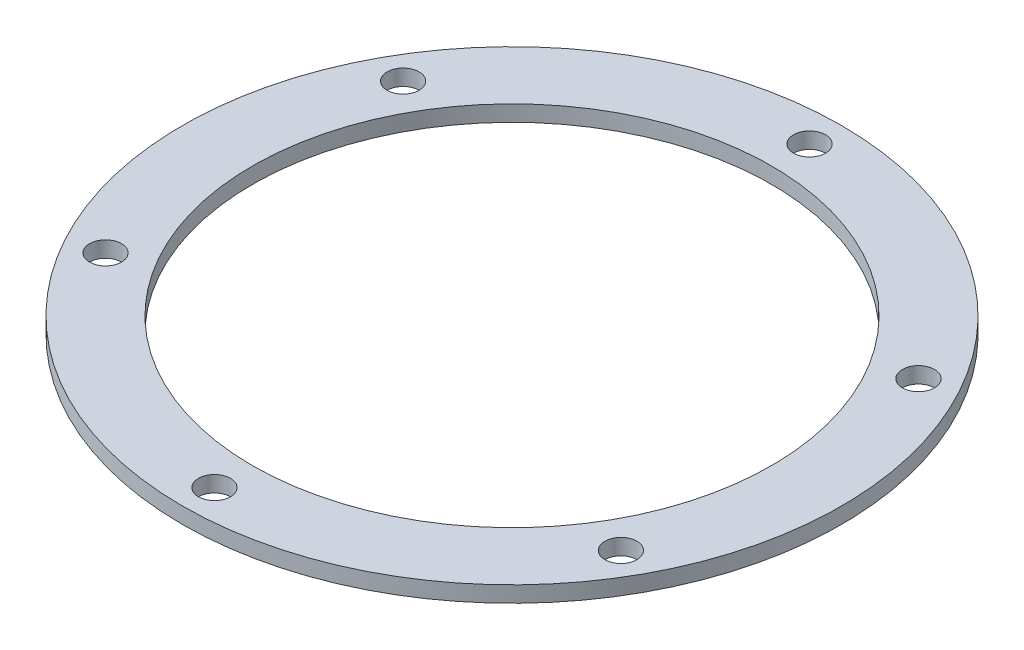
SolidWorks part; units mm, degrees
ref_plane "Front Plane" through (0, 0, 0) normal (0, 0, 1) x (1, 0, 0)
ref_plane "Top Plane" through (0, 0, 0) normal (0, 1, 0) x (1, 0, 0)
ref_plane "Right Plane" through (0, 0, 0) normal (1, 0, 0) x (0, 0, -1)
sketch "Sketch1" plane through (0, 0, 0) normal (0, 1, 0) x (1, 0, 0)
  circle A0 centre (0, 0) radius 41.195
  circle A1 centre (0, 0) radius 32.445
  circle A2 centre (0, 0) radius 37.195 construction
  circle A3 centre (0, 37.195) radius 2
  circle A4 centre (32.2118, 18.5975) radius 2
  circle A5 centre (32.2118, -18.5975) radius 2
  circle A6 centre (0, -37.195) radius 2
  circle A7 centre (-32.2118, -18.5975) radius 2
  circle A8 centre (-32.2118, 18.5975) radius 2
  point P16 (0, 0)
  point P18 (0, 0)
  dimension "D1" = 64.89
  dimension "D3" = 74.39
  dimension "D4" = 4
  dimension "D2" = 8.75
  dimension "D5" = 6
extrude "Boss-Extrude1" add sketch "Sketch1" along normal blind 2
equation "\"Ns\"= 20"
equation "\"Np\"= 40"
equation "\"Nr\"= \"Ns\" + 2 * \"Np\"'num teeth"
equation "\"num_planet\"= 3"
equation "\"module\"= 0.65"
equation "\"pressure angle\"= 20deg"
equation "\"h_a\"= 1 * \"module\"'addendum"
equation "\"h_b\"= 1.25 * \"module\"'dedendum"
equation "\"clr_tip_root\"= \"h_f\" - \"h_a\"'clearance of gear tooth tip and root"
equation "\"dp_s\"= \"module\" * \"Ns\"'PCD"
equation "\"db_s\"= \"dp_s\" * cos ( \"pressure angle\" )'base CD"
equation "\"fw_s_calc\"= 13mm'face width"
equation "\"alpha_s\"= sqr ( \"dp_s\" ^ 2 - \"db_s\" ^ 2 ) / \"db_s\" * 180 / pi - \"pressure angle\""
equation "\"beta_s\"= ( 360 / ( 4 * \"Ns\" ) - \"alpha_s\" ) * 2"
equation "\"dp_p\"= \"module\" * \"Np\"'PCD"
equation "\"db_p\"= \"dp_p\" * cos ( \"pressure angle\" )'base CD"
equation "\"fw_p\"= \"fw_r\""
equation "\"alpha_p\"= sqr ( \"dp_p\" ^ 2 - \"db_p\" ^ 2 ) / \"db_p\" * 180 / pi - \"pressure angle\""
equation "\"beta_p\"= ( 360 / ( 4 * \"Np\" ) - \"alpha_p\" ) * 2"
equation "\"pressure_angle\"= 20deg"
equation "\"h_f\"= 1.25 * \"module\"'dedendum"
equation "\"dp_r\"= \"module\" * \"Nr\"'PCD"
equation "\"db_r\"= \"dp_r\" * cos ( \"pressure_angle\" )'base CD"
equation "\"fw_r\"= 11.5mm'face width"
equation "\"alpha_r\"= sqr ( \"dp_r\" ^ 2 - \"db_r\" ^ 2 ) / \"db_r\" * 180 / pi - \"pressure_angle\""
equation "\"beta_r\"= ( 360 / ( 4 * \"Nr\" ) + \"alpha_r\" ) * 2"
equation "\"bearing_ID\"= \"module\" * ( \"Ns\" + \"Np\" ) + 10"
equation "\"bearing_OD\"= 1.18 * \"bearing_ID\" + 8.57"
equation "\"bearing_height\"= 0.09 * \"bearing_ID\" + 4.62"
equation "\"clearance_planet\"=1.5"
equation "\"case_dist\"= \"sec_carrier_thickness\" + \"clearance_planet\" + \"sun_coupler_hub_thickness\" - \"case_mounting_surface_height\""
equation "\"Motor_case_OD_max\"= \"case_mounting_PCD\" + \"case_mounting_hole_allen_socket_dia\" + \"clearance_case_mount_holes_shell_thickness\" * 2"
equation "\"case_mounting_PCD\"= \"motor_case_OD_base\" + \"case_mounting_hole_shift\" * 2"
equation "\"bearing mount thickness\"= \"output_mounting_hole_dia\" * 2"
equation "\"case_mounting_hole_dia\"=3"
equation "\"output_mounting_PCD\"= \"bearing_OD\" + \"bearing mount thickness\""
equation "\"output_mounting_hole_dia\"= 4"
equation "\"clearance_case_mount_holes_shell_thickness\"= 1"
equation "\"motor_case_OD_base\"= \"motor_OD\" + \"clearance_motor_and_case\" * 2 + \"Motor_case_thickness\" * 2"
equation "\"sec_carrier_thickness\"= 5"
equation "\"sun_coupler_hub_thickness\"= 4"
equation "\"clearance_sun_coupler_sec_carrier\"= 1.5"
equation "\"clearance_motor_and_case\"= 2.2"
equation "\"motor_OD\"= 72"
equation "\"Motor_case_thickness\"= 2"
equation "\"Motor_case_ID\"= \"motor_OD\" + \"clearance_motor_and_case\" * 2"
equation "\"case_mounting_hole_shift\"= \"case_mounting_hole_dia\" / 2 - 0.5"
equation "\"output_mounting_nut_wrench_size\"= 7"
equation "\"output_mounting_nut_thickness\"= 3.2"
equation "\"case_mounting_hole_allen_socket_dia\"= 5.5"
equation "\"output_mounting_nut_depth\"= 3"
equation "\"case_mounting_bolt_depth\"= 4.5"
equation "\"ring_radial_thickness\"= 5"
equation "\"ring_OD\"= \"Nr\" * \"module\" + \"ring_radial_thickness\" * 2"
equation "\"ring_to_chamfer_clearance\"= 2"
equation "\"Motor_case_OD_base_to_chamfer\"=5"
equation "\"pattern_offset_from_motor_case_OD_base\"= 3"
equation "\"pattern_bulge_dia\"= 3"
equation "\"pattern_num_bulge\"= 18"
equation "\"pattern_depth\"= 2"
equation "\"motor_height\"= 27"
equation "\"case_mounting_wrench_size\"= 5.5"
equation "\"case_mounting_nut_clearance\"= 2"
equation "\"base_plate_thickness\"= 4"
equation "\"case_mounting_nut_thickness\"= 2.4"
equation "\"case_mounting_surface_height\"= 4"
equation "\"motor_mount_hole_PCD\"= 32"
equation "\"motor_mount_hole_dia\"= 4"
equation "\"motor_mount_hole_num\"= 4"
equation "\"central_hole_offset_from_motor_mount_PCD\"= 5"
equation "\"wire_slot_dist_from_center\"= 30"
equation "\"wire_slot_length\"= 10"
equation "\"wire_slot_radius\"= 4"
equation "\"driver_upper_holes_dist_from_center\"= 23"
equation "\"driver_lower_holes_dist_from_center\"= 15"
equation "\"driver_side_holes_dist_from_center\"= 20"
equation "\"driver_mount_holes_dia\"= 2.5"
equation "\"driver_mount_inserts_OD\"= 3.5"
equation "\"driver_mount_thickness\"= 1.5"
equation "\"driver_mount_height\"= 4"
equation "\"air_flow_hole_offset\"= 3"
equation "\"planet_pin_bolt_dia\"= 5"
equation "\"planet_pin_socket_head_dia\"= 8.5"
equation "\"carrier_PCD\"= ( \"Np\" + \"Ns\" ) * \"module\""
equation "\"planet_shaft_dia\"= 8"
equation "\"planet_shaft_step_offset\"= 1"
equation "\"carrier_trapezoidal_support_sun_offset\"= 5"
equation "\"carrier_trapezoidal_support_hole_PCD_offset_bearing_ID\"= 4"
equation "\"carrier_trapezoidal_support_hole_dia\"= 3"
equation "\"carrier_trapezoidal_support_hole_socket_head_dia\"= 5.5"
equation "\"carrier_bearing_step_width\"= 1.5"
equation "\"standard_clearance_1_5mm\"=1.5"
equation "\"standard_fillet_1_5mm\"= 1.5"
equation "\"sun_shaft_bearing_OD\"= 16"
equation "\"sun_shaft_bearing_width\"= 4"
equation "\"standard_bearing_insertion_chamfer\"= 0.5"
equation "\"carrier_trapezoidal_support_hole_wrench_size\"= 5.5"
equation "\"planet_pin_bolt_wrench_size\"= 8"
equation "\"planet_bearing_OD\"= 12"
equation "\"planet_bearing_width\"= 3"
equation "\"planet_bore\"= 10"
equation "\"motor_output_hole_PCD\"= 22"
equation "\"motor_output_hole_dia\"= 3"
equation "\"motor_output_hole_num\"= 4"
equation "\"sun_shaft_bearing_ID\"= 8"
equation "\"sun_hub_dia\"= \"motor_output_hole_PCD\" + \"motor_output_hole_dia\" + \"standard_clearance_1_5mm\" * 4"
equation "\"sun_central_bolt_dia\"= 5"
equation "\"sun_central_bolt_socket_head_dia\"= 8.5"
equation "\"fw_s_used\"= \"fw_p\" + \"clearance_planet\" + \"sec_carrier_thickness\" + \"standard_clearance_1_5mm\""
equation "\"motor_output_hole_CSK_OD\"= 9'8.96 is exact value"
equation "\"motor_output_hole_CSK_head_height\"= 2.5"
equation "\"D1@Sketch1\"=\"bearing_OD\"-\"standard_clearance_1_5mm\""
equation "\"D2@Sketch1\"=\"bearing mount thickness\"+\"standard_clearance_1_5mm\"/2"
equation "\"D3@Sketch1\"=\"output_mounting_PCD\""
equation "\"D4@Sketch1\"=\"output_mounting_hole_dia\""
equation "\"bearing_retainer_thickness\"= 2"
equation "\"D1@Boss-Extrude1\"=\"bearing_retainer_thickness\""
